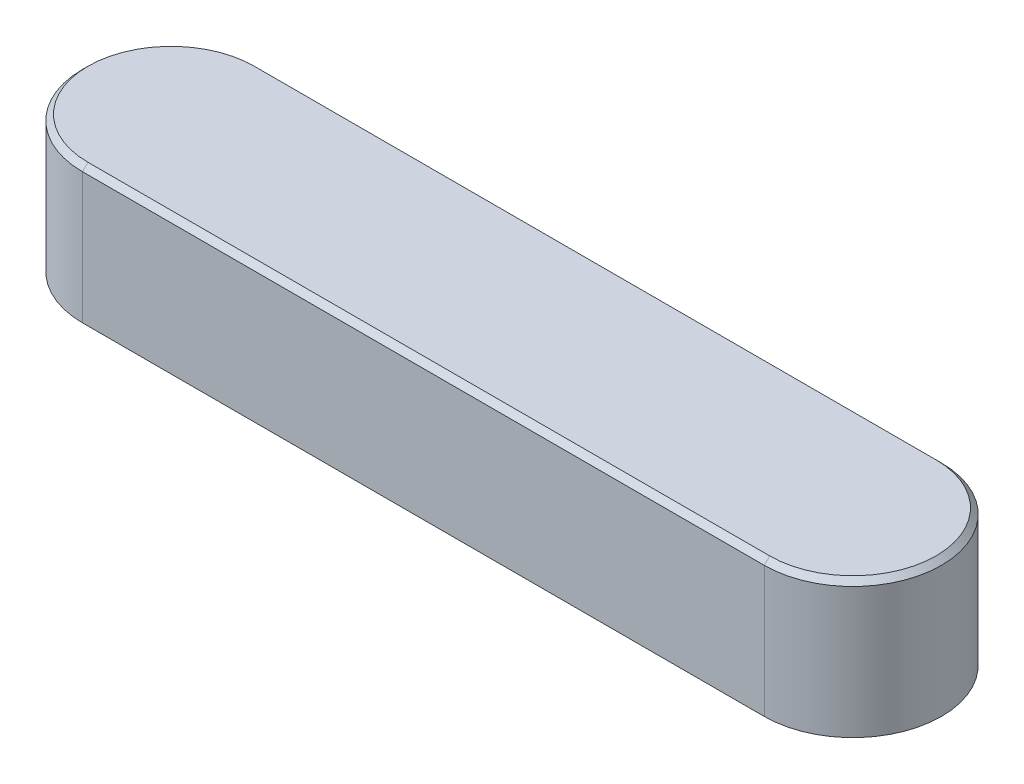
SolidWorks part; units mm, degrees
ref_plane "Plan de face" through (0, 0, 0) normal (0, 0, 1) x (1, 0, 0)
ref_plane "Plan de dessus" through (0, 0, 0) normal (0, 1, 0) x (1, 0, 0)
ref_plane "Plan de droite" through (0, 0, 0) normal (1, 0, 0) x (0, 0, -1)
sketch "Esquisse2" plane through (0, 0, 0) normal (0, 1, 0) x (1, 0, 0)
  line L0 (-8.642, 0) -> (16.358, 0) construction
  line L1 (-8.642, 3.25) -> (16.358, 3.25)
  line L2 (-8.642, -3.25) -> (16.358, -3.25)
  arc A0 (-8.642, 3.25) -> (-8.642, -3.25) centre (-8.642, 0) ccw
  arc A1 (16.358, -3.25) -> (16.358, 3.25) centre (16.358, 0) ccw
  point P3 (3.858, 0)
  dimension "D2" = 3.25
  dimension "D1" = 25
extrude "Boss.-Extru.1" add sketch "Esquisse2" along normal blind 5
chamfer "Chanfrein1" distance 0.2 angle 45 4 edges at (3.858, 5, -3.25) (19.608, 5, 0) (3.858, 5, 3.25) (-11.892, 5, 0)
